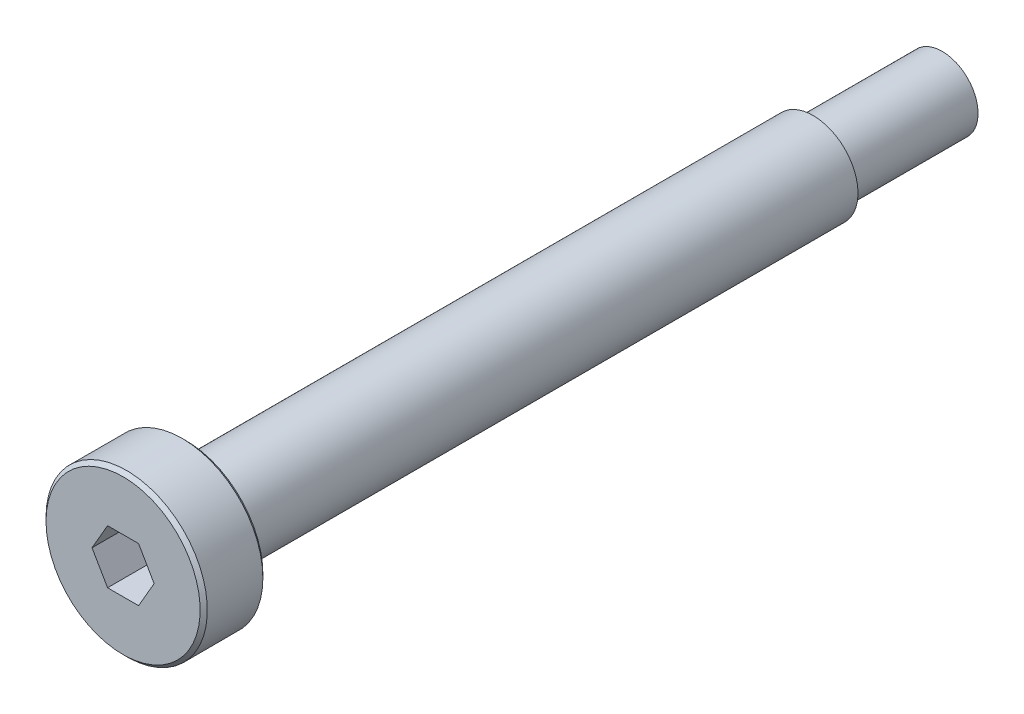
SolidWorks part; units mm, degrees
material "AISI 304"
ref_plane "前视基准面" through (0, 0, 0) normal (1, 0, 0) x (0, 1, 0)
ref_plane "上视基准面" through (0, 0, 0) normal (0, 0, 1) x (0, 1, 0)
ref_plane "右视基准面" through (0, 0, 0) normal (0, 1, 0) x (-1, 0, 0)
other "Configuration Table"
sketch "草图1" plane through (0, 0, 0) normal (1, 0, 0) x (0, 1, 0)
  line L0 (0, 0) -> (-4.5, 0)
  line L1 (-4.5, 0) -> (-4.5, -3.5)
  line L2 (-4.5, -3.5) -> (-2.5, -3.5)
  line L3 (-2.5, -3.5) -> (-2.5, -38.5)
  line L4 (-2.5, -38.5) -> (-2, -38.5)
  line L5 (-2, -38.5) -> (-2, -45.7)
  line L6 (-2, -45.7) -> (0, -45.7)
  line L7 (0, -45.7) -> (0, 0)
  point P8 (-2.25, -38.5)
  dimension "D1" = 3.5
  dimension "D2" = 35
  dimension "D3" = 7.2
  dimension "D4" = 2
  dimension "D5" = 4.5
  dimension "D6" = 2.5
revolve "旋转1" add sketch "草图1" angle 360 about L7
cosmetic thread "装饰螺纹线1"
sketch "草图2" plane through (0, 0, 0) normal (0, 0, 1) x (1, 0, 0)
  line L0 (0, 0) -> (1.7321, 0) construction
  line L1 (1.7321, 0) -> (0.866, 1.5)
  line L2 (0.866, 1.5) -> (-0.866, 1.5)
  line L3 (-0.866, 1.5) -> (-1.7321, 0)
  line L4 (-1.7321, 0) -> (-0.866, -1.5)
  line L5 (-0.866, -1.5) -> (0.866, -1.5)
  line L6 (0.866, -1.5) -> (1.7321, 0)
  circle A0 centre (0, 0) radius 1.5 construction
  dimension "D1" = 3
extrude "切除-拉伸1" cut sketch "草图2" against normal blind 3
chamfer "倒角1" distance 0.2 angle 45 2 edges at (-4.5, 0, -3.5) (-4.5, 0, 0)
